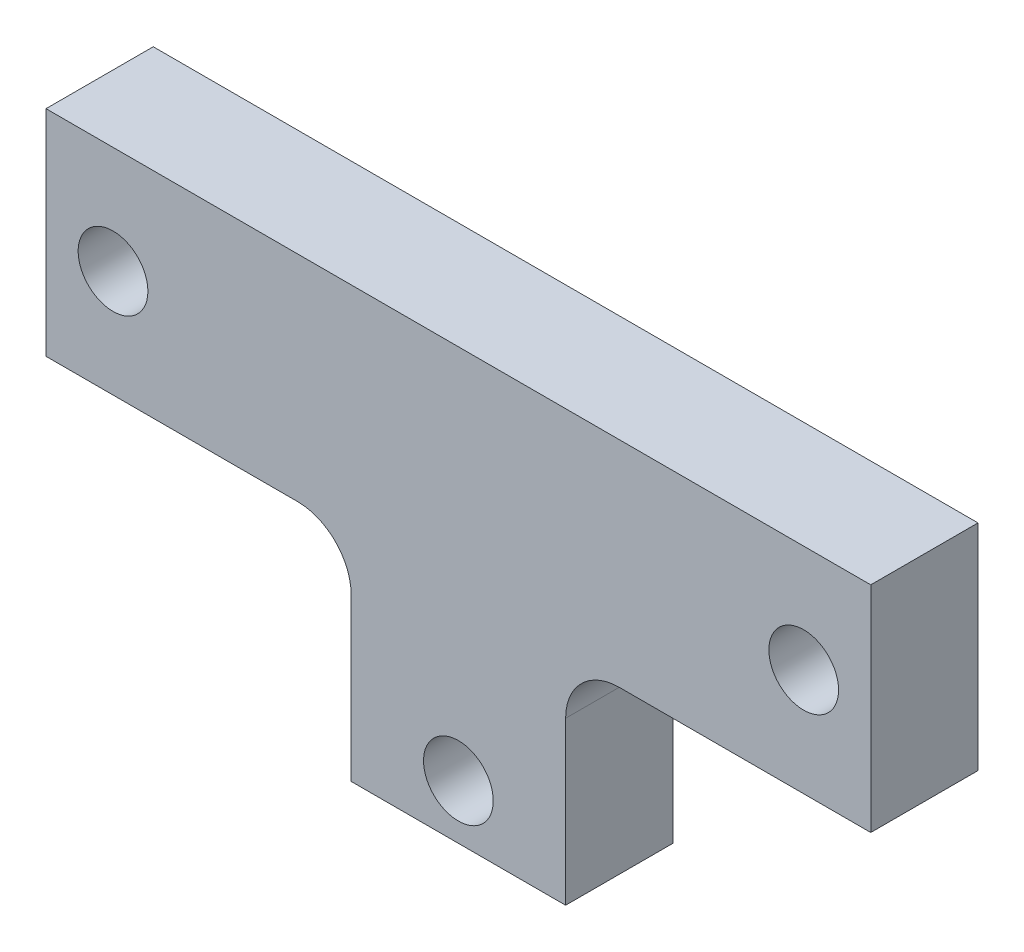
SolidWorks part; units mm, degrees
ref_plane "Front Plane" through (0, 0, 0) normal (0, 0, 1) x (1, 0, 0)
ref_plane "Top Plane" through (0, 0, 0) normal (0, 1, 0) x (1, 0, 0)
ref_plane "Right Plane" through (0, 0, 0) normal (1, 0, 0) x (0, 0, -1)
sketch "Sketch1" plane through (0, 0, 0) normal (0, 0, 1) x (1, 0, 0)
  line L0 (0, 0) -> (0, -20.1)
  line L1 (0, -20.1) -> (20, -20.1)
  line L2 (20, -20.1) -> (20, 0)
  line L3 (20, 0) -> (46.45, 0)
  line L4 (46.45, 0) -> (46.45, 20)
  line L5 (46.45, 20) -> (-26.45, 20)
  line L6 (-26.45, 20) -> (-26.45, 0)
  line L7 (-26.45, 0) -> (0, 0)
  dimension "D1" = 72.9
  dimension "D2" = 20
  dimension "D3" = 26.45
  dimension "D4" = 20
  dimension "D5" = 20.1
extrude "Boss-Extrude1" add sketch "Sketch1" along normal blind 10
sketch "Sketch2" plane through (0, 0, 10) normal (0, 0, 1) x (1, 0, 0)
  line L0 (10, 20) -> (10, 12.133) construction
  line L1 (46.45, 20) -> (-26.45, 20) construction
  line L2 (-26.45, 0) -> (0, 0) construction
  line L3 (-26.45, 20) -> (-17.95, 20) construction
  line L4 (-26.45, 20) -> (-26.45, 0) construction
  line L5 (-26.45, 0) -> (-17.95, 0) construction
  line L6 (-17.95, 20) -> (-17.95, 0) construction
  line L7 (-26.45, 20) -> (-17.95, 0) construction
  line L8 (-26.45, 0) -> (-17.95, 20) construction
  line L9 (20, -20.1) -> (20, 0) construction
  line L10 (0, -20.1) -> (20, -20.1) construction
  line L11 (0, -20.1) -> (0, -10) construction
  line L12 (0, -10) -> (20, -10) construction
  line L13 (20, -20.1) -> (20, -10) construction
  line L14 (0, -20.1) -> (20, -10) construction
  line L15 (0, -10) -> (20, -20.1) construction
  circle A0 centre (-22.2, 10) radius 2
  circle A1 centre (10, -15.05) radius 2
  circle A2 centre (42.2, 10) radius 2
  point P8 (-22.2, 10)
  point P16 (10, -15.05)
  dimension "D3" = 4
  dimension "D4" = 4
  dimension "D1" = 8.5
  dimension "D2" = 10.1
extrude "Cut-Extrude1" cut sketch "Sketch2" against normal through all
sketch "Sketch3" plane through (0, 0, 10) normal (0, 0, 1) x (1, 0, 0)
  circle A0 centre (-22.2, 10) radius 3.25
  circle A1 centre (42.2, 10) radius 3.25
  circle A2 centre (10, -15.05) radius 3.25
  dimension "D1" = 6.5
  dimension "D2" = 6.5
  dimension "D3" = 6.5
extrude "Cut-Extrude2" cut sketch "Sketch3" against normal blind 6
fillet "Fillet1" radius 5 2 edges at (0, 0, 5) (20, 0, 5)
sketch "Sketch4" plane through (46.45, 0, 0) normal (1, 0, 0) x (0, 0, -1)
  line L1 (-10, 20) -> (0, 20)
  line L2 (-10, 20) -> (-10, 0)
  line L3 (-10, 0) -> (0, 0)
  line L4 (0, 20) -> (0, 0)
  line L5 (-10, 20) -> (0, 0) construction
  line L6 (-10, 0) -> (0, 20) construction
  point P4 (-5, 10)
extrude "Boss-Extrude2" add sketch "Sketch4" along normal blind 2
sketch "Sketch5" plane through (-26.45, 0, 0) normal (-1, 0, 0) x (0, 0, 1)
  line L1 (0, 20) -> (10, 20)
  line L2 (0, 20) -> (0, 0)
  line L3 (0, 0) -> (10, 0)
  line L4 (10, 20) -> (10, 0)
  line L5 (0, 20) -> (10, 0) construction
  line L6 (0, 0) -> (10, 20) construction
  point P4 (5, 10)
extrude "Boss-Extrude3" add sketch "Sketch5" along normal blind 2
